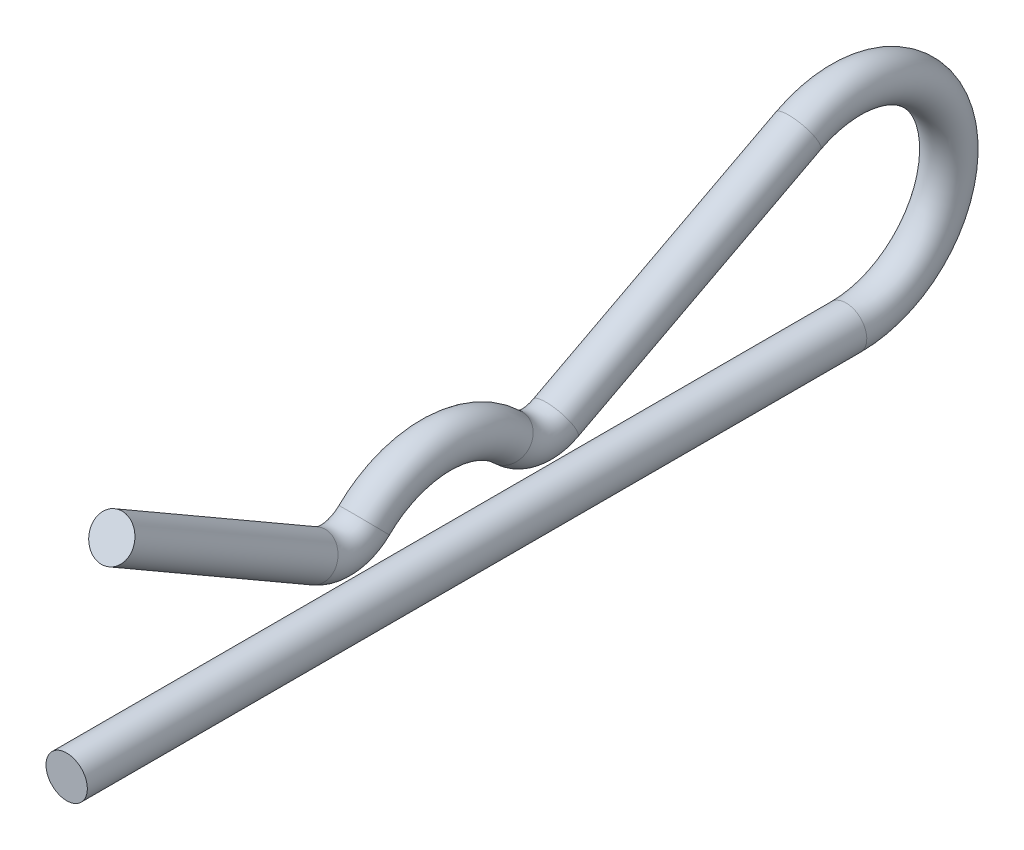
SolidWorks part; units mm, degrees
ref_plane "Front" through (0, 0, 0) normal (0, 0, 1) x (1, 0, 0)
ref_plane "Top" through (0, 0, 0) normal (0, 1, 0) x (1, 0, 0)
ref_plane "Right" through (0, 0, 0) normal (1, 0, 0) x (0, 0, -1)
sketch "Sketch1" plane through (0, 0, 0) normal (0, 0, 1) x (1, 0, 0)
  circle A0 centre (0, 0) radius 0.8001
sketch "Sketch2" plane through (0, 0, 0) normal (1, 0, 0) x (0, 0, -1)
  line L0 (0, 0) -> (30.1498, 0)
  line L1 (10.3963, 3.9751) -> (18.1787, 3.9751) construction
  line L2 (34.925, 0) -> (34.925, 3.9751) construction
  line L3 (34.925, 3.9751) -> (34.1249, 3.9751) construction
  line L5 (34.925, 0) -> (0, 0) construction
  line L6 (9.6026, 2.6003) -> (1.7462, 7.1361)
  line L7 (14.2875, 3.9751) -> (14.2875, 0) construction
  line L13 (28.3027, 7.495) -> (18.9163, 2.5694)
  circle A0 centre (30.1498, 3.9751) radius 3.175 construction
  arc A1 (17.0682, 2.8407) -> (11.5068, 2.8407) centre (14.2875, 0) ccw
  arc A6 (11.5068, 2.8407) -> (9.6026, 2.6003) centre (10.3963, 3.9751) cw
  arc A8 (18.9163, 2.5694) -> (17.0682, 2.8407) centre (18.1787, 3.9751) cw
  arc A9 (30.1498, 0) -> (28.3027, 7.495) centre (30.1498, 3.9751) ccw
  dimension "D1" = 1.5875
  dimension "D2" = 14.2875
  dimension "D5" = 1.7463
  dimension "D9" = 30
  dimension "D11" = 0.8001
  dimension "D3" = 0.8001
sweep "Sweep1" add profiles "Sketch1" path "Sketch2"
equation "\"D11@Sketch2\" = \"WireOD@Sketch1\"/2"
equation "\"D1@Sketch2\" = \"EyeID@Sketch2\"/4"
equation "\"D3@Sketch2\" = \"D11@Sketch2\""
equation "\"D2@Sketch2\" = (\"Length@Sketch2\"-\"EyeID@Sketch2\")/2"
equation "\"D5@Sketch2\" = \"Length@Sketch2\"*.05"
